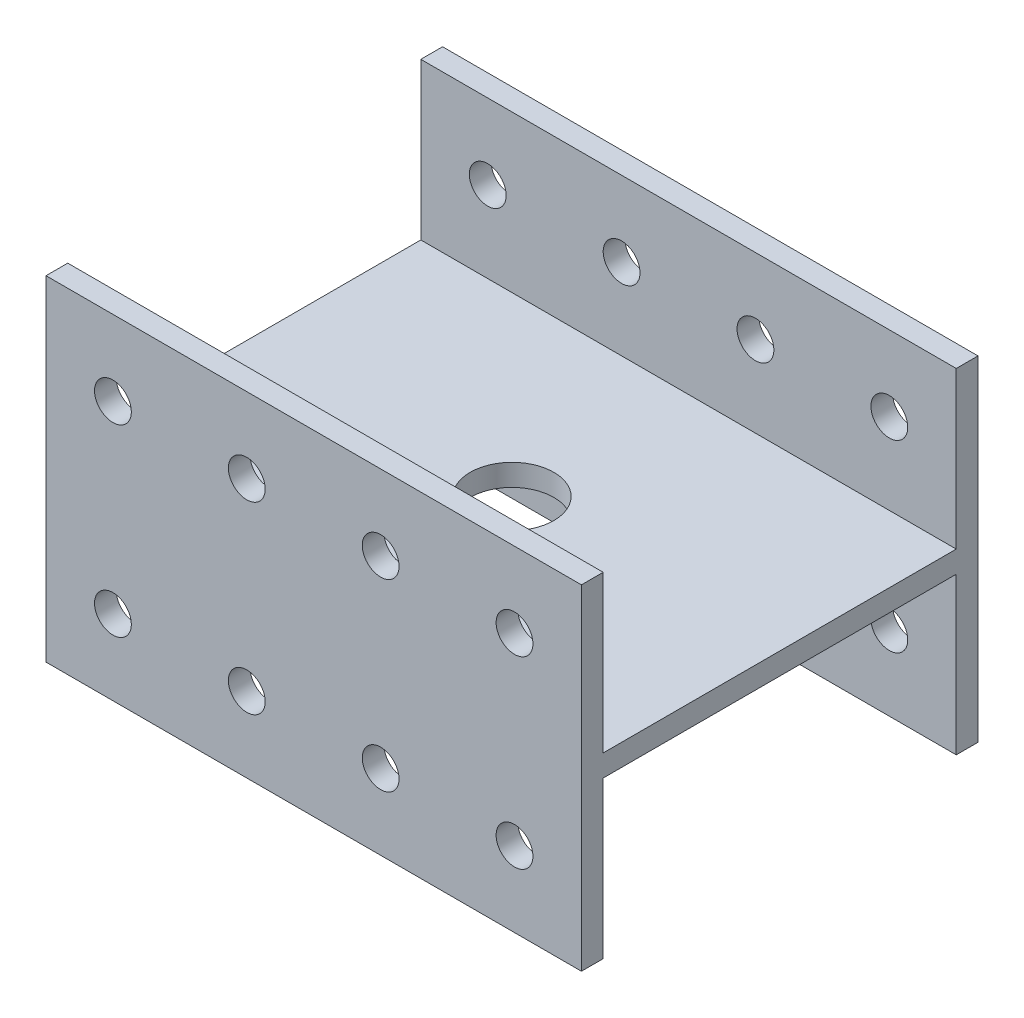
SolidWorks part; units mm, degrees
ref_plane "前视基准面" through (0, 0, 0) normal (0, 0, 1) x (1, 0, 0)
ref_plane "上视基准面" through (0, 0, 0) normal (0, 1, 0) x (1, 0, 0)
ref_plane "右视基准面" through (0, 0, 0) normal (1, 0, 0) x (0, 0, -1)
sketch "草图1" plane through (0, 0, 0) normal (0, 0, 1) x (1, 0, 0)
  line L1 (0, 200) -> (320, 200)
  line L2 (0, 200) -> (0, 0)
  line L3 (0, 0) -> (320, 0)
  line L4 (320, 200) -> (320, 0)
  dimension "D1" = 320
  dimension "D2" = 200
extrude "拉伸1" add sketch "草图1" along normal blind 237
sketch "草图2" plane through (0, 0, 237) normal (0, 0, 1) x (1, 0, 0)
  line L0 (0, 0) -> (320, 0) construction
  line L1 (0, 200) -> (0, 0) construction
  circle A0 centre (40, 45) radius 11
  dimension "D1" = 45
  dimension "D2" = 40
extrude "切除-拉伸1" cut sketch "草图2" against normal through all
pattern_linear "阵列(线性)1" count 4 spacing 80 along (1, 0, 0) count 2 spacing 110 along (0, 1, 0) of "切除-拉伸1"
sketch "草图6" plane through (0, 0, 0) normal (-1, 0, 0) x (0, 0, 1)
  line L0 (237, 200) -> (0, 200) construction
  line L1 (13, 200) -> (224, 200)
  line L2 (13, 200) -> (13, 106.5)
  line L3 (13, 106.5) -> (224, 106.5)
  line L4 (224, 200) -> (224, 106.5)
  line L5 (0, 200) -> (0, 0) construction
  line L6 (237, 0) -> (0, 0) construction
  line L7 (13, 0) -> (224, 0)
  line L8 (13, 0) -> (13, 93.5)
  line L9 (13, 93.5) -> (224, 93.5)
  line L10 (224, 0) -> (224, 93.5)
  dimension "D1" = 211
  dimension "D2" = 93.5
  dimension "D3" = 13
extrude "切除-拉伸3" cut sketch "草图6" against normal through all
sketch "草图7" plane through (0, 106.5, 0) normal (0, 1, 0) x (1, 0, 0)
  line L0 (0, -13) -> (0, -224) construction
  line L1 (320, 0) -> (0, 0) construction
  circle A0 centre (160, -118.5) radius 25
  point P2 (0, -118.5)
  dimension "D1" = 160
  dimension "D2" = 118.5
extrude "切除-拉伸4" cut sketch "草图7" against normal through all
